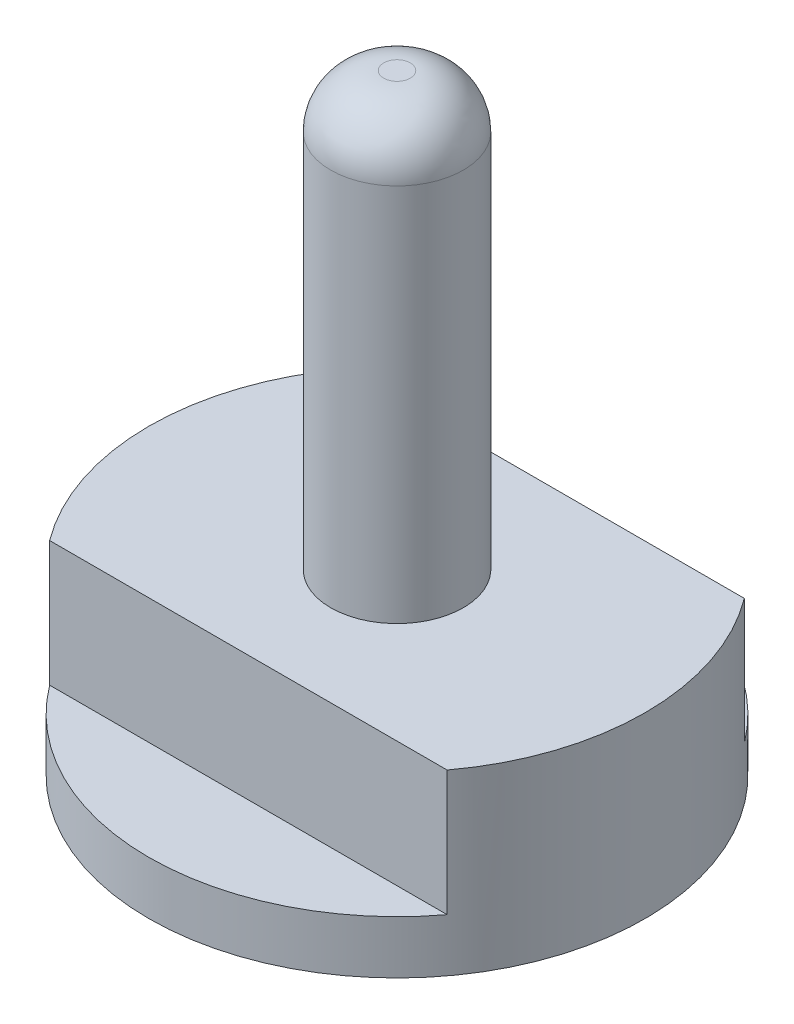
SolidWorks part; units mm, degrees
ref_plane "Plane1" through (0, 0, 0) normal (0, 0, 1) x (1, 0, 0)
ref_plane "Plane2" through (0, 0, 0) normal (0, 1, 0) x (1, 0, 0)
ref_plane "Plane3" through (0, 0, 0) normal (1, 0, 0) x (0, 0, -1)
other "Configuration Table"
sketch "Sketch2" plane through (0, 3.36, 0) normal (0, 1, 0) x (-1, 0, 0)
  line L0 (-3.7437, 0) -> (3.7437, 0) construction
  line L1 (-3.7437, 5.6) -> (3.7437, 5.6) construction
  line L2 (-3.7437, 0) -> (3.7437, 0)
  line L3 (-3.7437, 5.6) -> (3.7437, 5.6)
  arc A0 (3.7437, 0) -> (3.7437, 5.6) centre (0, 2.8) ccw construction
  arc A1 (-3.7437, 5.6) -> (-3.7437, 0) centre (0, 2.8) ccw construction
  arc A2 (3.7437, 0) -> (3.7437, 5.6) centre (0, 2.8) ccw
  arc A3 (-3.7437, 5.6) -> (-3.7437, 0) centre (0, 2.8) ccw
extrude "Base-Extrude" add sketch "Sketch2" against normal up to surface (3.36 mm away)
sketch "Sketch3" plane through (0, 3.36, 0) normal (0, 1, 0) x (-1, 0, 0)
  circle A0 centre (0, 2.8) radius 1.25
  arc A1 (3.7437, 0) -> (3.7437, 5.6) centre (0, 2.8) ccw construction
  dimension "D1" = 2.5
extrude "Boss-Extrude1" add sketch "Sketch3" along normal blind 8.14
fillet "Fillet1" radius 1 1 edges at (0, 11.5, 4.05)
sketch "Sketch4" plane through (0, 0, 0) normal (0, -1, 0) x (1, 0, 0)
  circle A0 centre (0, 2.8) radius 4.675
  arc A1 (3.7437, 0) -> (3.7437, 5.6) centre (0, 2.8) ccw construction
extrude "Boss-Extrude2" add sketch "Sketch4" against normal blind 1
sketch "Sketch5" plane through (0, 0, 0) normal (0, -1, 0) x (1, 0, 0)
  circle A1 centre (0, 2.8) radius 1.675
  circle A2 centre (0, 2.8) radius 1.675
  circle A3 centre (0, 2.8) radius 1.175
  circle A4 centre (0, 2.8) radius 1.175
  dimension "D1" = 3
  dimension "D2" = 3.5
extrude "Boss-Extrude3" add sketch "Sketch5" along normal blind 2
